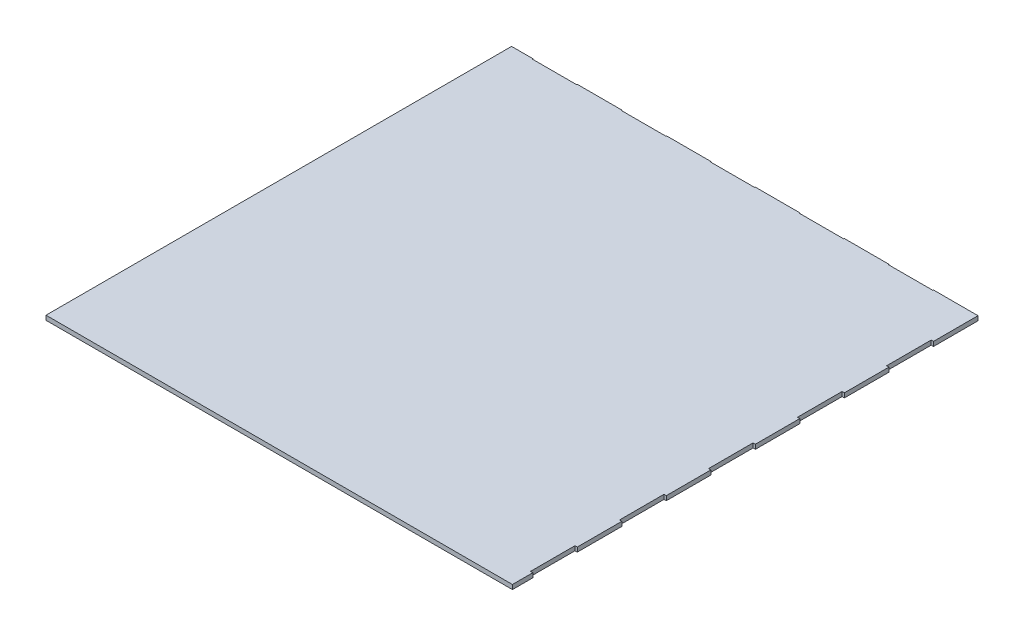
SolidWorks part; units mm, degrees
ref_plane "Front Plane" through (0, 0, 0) normal (0, 0, 1) x (1, 0, 0)
ref_plane "Top Plane" through (0, 0, 0) normal (0, 1, 0) x (1, 0, 0)
ref_plane "Right Plane" through (0, 0, 0) normal (1, 0, 0) x (0, 0, -1)
sketch "Sketch1" plane through (0, 0, 0) normal (0, 1, 0) x (1, 0, 0)
  line L1 (-315, -315) -> (315, -315)
  line L2 (-315, -315) -> (-315, 315)
  line L3 (-315, 315) -> (315, 315)
  line L4 (315, -315) -> (315, 315)
  line L5 (0, 315) -> (0, -315) construction
  line L6 (-315, 0) -> (315, 0) construction
  point P0 (0, 0)
extrude "Boss-Extrude1" add sketch "Sketch1" along normal blind 3
ref_plane "Plane1" through (0, 0, 285) normal (0, 0, 1) x (1, 0, 0)
sketch "Sketch3" plane through (0, 3, 0) normal (0, 1, 0) x (1, 0, 0)
  line L0 (-315, 315) -> (-315, -315) construction
  line L1 (-315, -285.0068) -> (-312, -285.0068)
  line L2 (-315, -285.0068) -> (-315, -255.0068)
  line L3 (-315, -255.0068) -> (-312, -255.0068)
  line L4 (-312, -285.0068) -> (-312, -255.0068)
  dimension "D1" = 30
  dimension "D2" = 3
extrude "Cut-Extrude2" cut sketch "Sketch3" against normal blind 3
pattern_linear "LPattern2" count 10 spacing 60 along (0, 0, -1) of "Cut-Extrude2"
ref_plane "Plane2" through (0.72, 0, 0) normal (1, 0, 0) x (0, 0, -1)
mirror "Mirror1" about plane through (0.72, 0, 0) normal (1, 0, 0) of "LPattern2", "Cut-Extrude2"
ref_plane "Plane3" through (-285, 0, 0) normal (-1, 0, 0) x (0, 0, 1)
sketch "Sketch5" plane through (0, 3, 0) normal (0, 1, 0) x (1, 0, 0)
  line L0 (-315, -315) -> (315, -315) construction
  line L1 (-285.0003, -315) -> (-255.0003, -315)
  line L2 (-285.0003, -315) -> (-285.0003, -312)
  line L3 (-285.0003, -312) -> (-255.0003, -312)
  line L4 (-255.0003, -315) -> (-255.0003, -312)
  dimension "D1" = 30
  dimension "D2" = 3
extrude "Cut-Extrude3" cut sketch "Sketch5" against normal blind 3
pattern_linear "LPattern3" count 10 spacing 60 along (1, 0, 0) of "Cut-Extrude3"
ref_plane "Plane4" through (0, 0, -1.29) normal (0, 0, 1) x (1, 0, 0)
mirror "Mirror2" about plane through (0, 0, -1.29) normal (0, 0, 1) of "LPattern3", "Cut-Extrude3"
other "SurfaceCut1"
other "SurfaceCut2"
